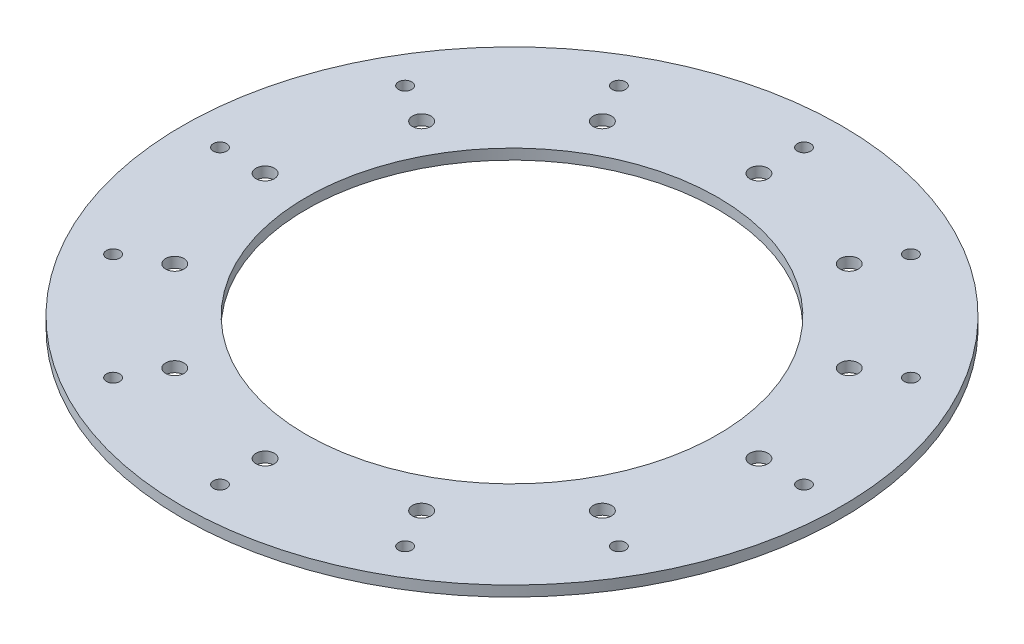
SolidWorks part; units mm, degrees
material "1060 Alloy"
ref_plane "Ebene vorne" through (0, 0, 0) normal (0, 0, 1) x (1, 0, 0)
ref_plane "Ebene oben" through (0, 0, 0) normal (0, 1, 0) x (1, 0, 0)
ref_plane "Ebene rechts" through (0, 0, 0) normal (1, 0, 0) x (0, 0, -1)
sketch "Sketch1" plane through (0, 0, 0) normal (0, 1, 0) x (1, 0, 0)
  circle A0 centre (0, 0) radius 49.3
  circle A1 centre (0, 0) radius 79
  dimension "D1" = 158
  dimension "D2" = 98.6
extrude "Boss-Extrude1" add sketch "Sketch1" along normal blind 2.5
sketch "Sketch2" plane through (0, 2.5, 0) normal (0, 1, 0) x (1, 0, 0)
  circle A0 centre (0, 70) radius 1.6
  circle A1 centre (35, 60.6218) radius 1.6
  circle A2 centre (60.6218, 35) radius 1.6
  circle A3 centre (70, 0) radius 1.6
  circle A4 centre (60.6218, -35) radius 1.6
  circle A5 centre (35, -60.6218) radius 1.6
  circle A6 centre (0, -70) radius 1.6
  circle A7 centre (-35, -60.6218) radius 1.6
  circle A8 centre (-60.6218, -35) radius 1.6
  circle A9 centre (-70, 0) radius 1.6
  circle A10 centre (-60.6218, 35) radius 1.6
  circle A11 centre (-35, 60.6218) radius 1.6
  point P28 (0, 0)
  dimension "D1" = 3.2
  dimension "D2" = 70
  dimension "D3" = 12
extrude "Cut-Extrude1" cut sketch "Sketch2" against normal through all
sketch "Sketch3" plane through (0, 2.5, 0) normal (0, 1, 0) x (1, 0, 0)
  circle A0 centre (0, 59.18) radius 2.2
  circle A1 centre (29.59, 51.2514) radius 2.2
  circle A2 centre (51.2514, 29.59) radius 2.2
  circle A3 centre (59.18, 0) radius 2.2
  circle A4 centre (51.2514, -29.59) radius 2.2
  circle A5 centre (29.59, -51.2514) radius 2.2
  circle A6 centre (0, -59.18) radius 2.2
  circle A7 centre (-29.59, -51.2514) radius 2.2
  circle A8 centre (-51.2514, -29.59) radius 2.2
  circle A9 centre (-59.18, 0) radius 2.2
  circle A10 centre (-51.2514, 29.59) radius 2.2
  circle A11 centre (-29.59, 51.2514) radius 2.2
  point P28 (0, 0)
  dimension "D1" = 4.4
  dimension "D3" = 118.36
  dimension "D2" = 12
extrude "Cut-Extrude2" cut sketch "Sketch3" against normal through all
